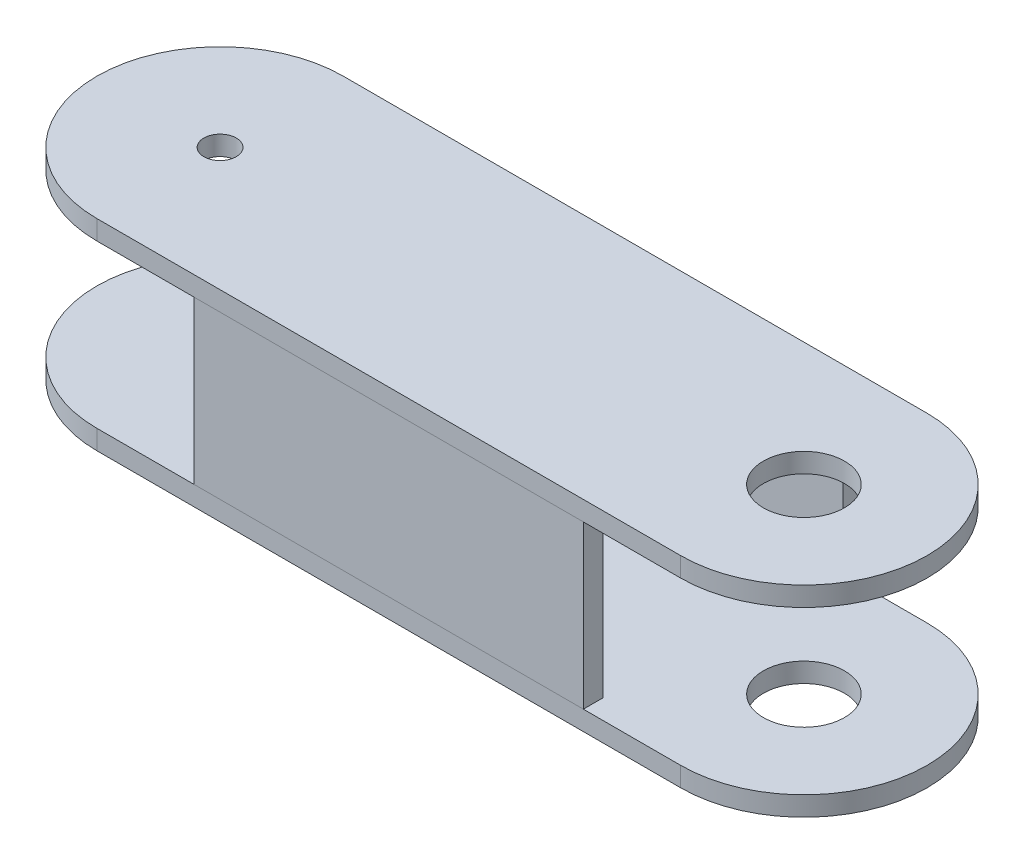
SolidWorks part; units mm, degrees
material "Acrylic (Medium-high impact)"
ref_plane "Front Plane" through (0, 0, 0) normal (0, 0, 1) x (1, 0, 0)
ref_plane "Top Plane" through (0, 0, 0) normal (0, 1, 0) x (1, 0, 0)
ref_plane "Right Plane" through (0, 0, 0) normal (1, 0, 0) x (0, 0, -1)
sketch "Sketch2" plane through (0, 0, 0) normal (0, 1, 0) x (1, 0, 0)
  line L0 (-90, 0) -> (90, 0) construction
  line L1 (-90, 38) -> (90, 38)
  line L2 (-90, -38) -> (90, -38)
  arc A0 (-90, 38) -> (-90, -38) centre (-90, 0) ccw
  arc A1 (90, -38) -> (90, 38) centre (90, 0) ccw
  circle A2 centre (90, 0) radius 12.5
  circle A3 centre (-90, 0) radius 5
  point P2 (0, 0)
  dimension "D3" = 25
  dimension "D4" = 10
  dimension "D1" = 180
  dimension "D2" = 76
extrude "Boss-Extrude1" add sketch "Sketch2" along normal mid plane 62
sketch "Sketch3" plane through (0, 0, 0) normal (1, 0, 0) x (0, 0, -1)
  line L0 (38, 31) -> (38, -31) construction
  line L1 (-38, 25) -> (38, 25)
  line L2 (-38, 25) -> (-38, -25)
  line L3 (-38, -25) -> (38, -25)
  line L4 (38, 25) -> (38, -25)
  line L5 (-38, 25) -> (38, -25) construction
  line L6 (-38, -25) -> (38, 25) construction
  line L7 (38, 31) -> (-38, 31) construction
  point P0 (0, 0)
  dimension "D1" = 6
extrude "Cut-Extrude1" cut sketch "Sketch3" against normal through all both and the other way through all
sketch "Sketch4" plane through (0, -25, 0) normal (0, 1, 0) x (1, 0, 0)
  line L0 (90, 38) -> (-90, 38) construction
  line L1 (-70, 38) -> (70, 38)
  line L2 (-70, 38) -> (-70, 32)
  line L3 (-70, 32) -> (70, 32)
  line L4 (70, 38) -> (70, 32)
  line L5 (-90, -38) -> (90, -38) construction
  line L6 (-60, -38) -> (60, -38)
  line L7 (-60, -38) -> (-60, -32)
  line L8 (-60, -32) -> (60, -32)
  line L9 (60, -38) -> (60, -32)
  line L10 (0, 0) -> (0, 38) construction
  dimension "D1" = 6
  dimension "D2" = 120
  dimension "D3" = 140
extrude "Boss-Extrude2" add sketch "Sketch4" along normal up to next separate body
